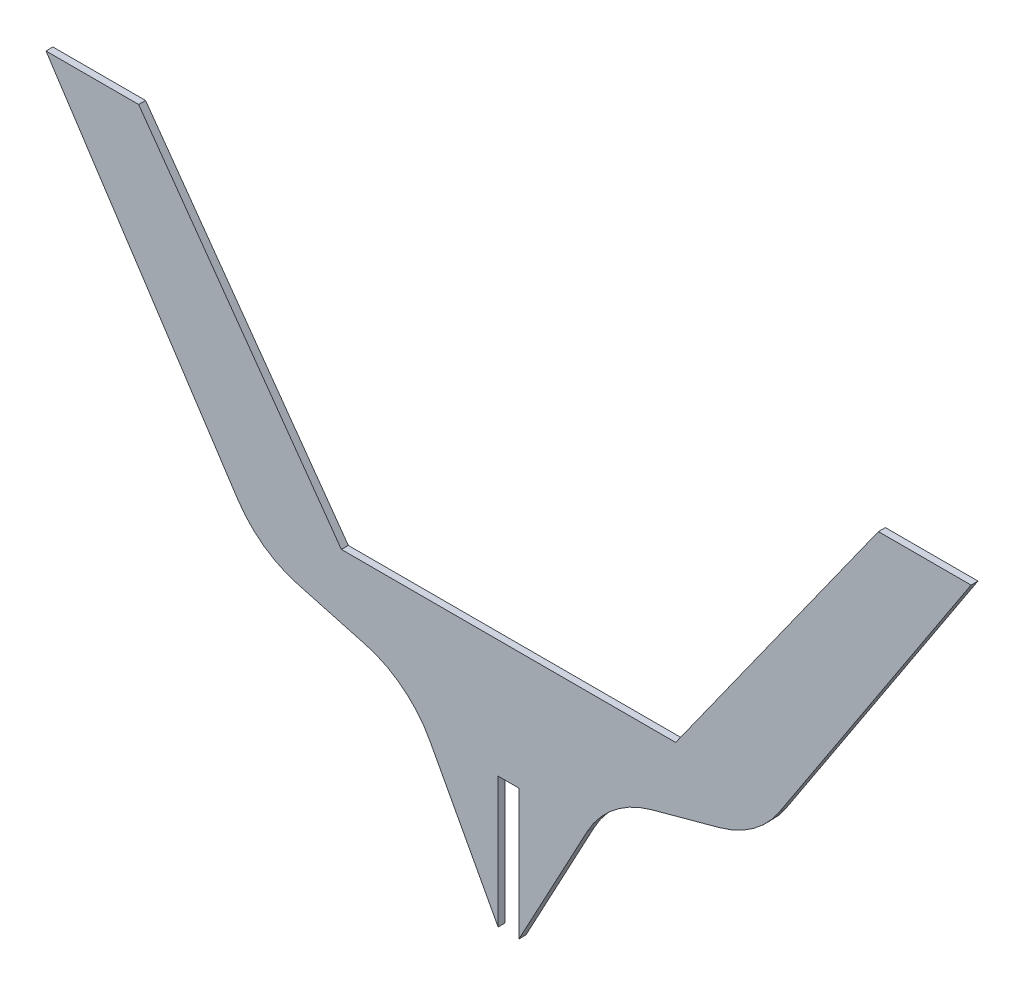
SolidWorks part; units mm, degrees
ref_plane "Plan de face" through (0, 0, 0) normal (0, 0, 1) x (1, 0, 0)
ref_plane "Plan de dessus" through (0, 0, 0) normal (0, 1, 0) x (1, 0, 0)
ref_plane "Plan de droite" through (0, 0, 0) normal (1, 0, 0) x (0, 0, -1)
sketch "Esquisse3" plane through (0, 0, 0) normal (0, 0, 1) x (1, 0, 0)
  line L46 (45.5101, -47.7781) -> (133.182, -170.5717)
  line L48 (5.4584, -47.7781) -> (97.7493, -188.5196)
  line L49 (97.7493, -188.5196) -> (162.3121, -206.0781)
  line L50 (162.3121, -206.0781) -> (200.9584, -278.0781)
  line L51 (200.9584, -278.0781) -> (200.9584, -221.5781)
  line L54 (205.4584, -221.5781) -> (205.4584, 18.2487) construction
  line L67 (5.4584, -47.7781) -> (45.5101, -47.7781)
  line L68 (133.182, -170.5717) -> (277.7348, -170.5717)
  line L69 (200.9584, -221.5781) -> (209.9584, -221.5781)
  line L70 (405.4584, -47.7781) -> (365.4068, -47.7781)
  line L71 (209.9584, -278.0781) -> (209.9584, -221.5781)
  line L72 (248.6048, -206.0781) -> (209.9584, -278.0781)
  line L73 (313.1676, -188.5196) -> (248.6048, -206.0781)
  line L74 (405.4584, -47.7781) -> (313.1676, -188.5196)
  line L75 (365.4068, -47.7781) -> (277.7348, -170.5717)
  point P6 (205.4584, -170.5717)
  point P16 (55.0051, -108.12)
  point P17 (153.6603, -162.8768)
  point P18 (77.7707, -130.3527)
  point P19 (0, 0)
  point P20 (107.4419, -120.2022)
  point P21 (57.3184, -48.3686)
  point P23 (0, 0)
  point P24 (67.9459, -131.0269)
  point P25 (113.408, -119.8089)
  point P26 (45.5101, -47.7781)
  point P27 (108.0942, -124.5323)
  point P28 (162.3121, -221.5781)
  point P29 (97.7493, -188.5196)
  point P30 (123.3054, -172.3789)
  point P31 (138.7637, -169.7743)
  point P32 (133.182, -170.5717)
  dimension "D1" = 400
  dimension "D2" = 9
  dimension "D3" = 173.8
  dimension "D4" = 56.5
extrude "Boss.-Extru.3" add sketch "Esquisse3" along normal blind 3
fillet "Congé1" radius 45 4 edges at (313.1676, -188.5196, 1.5) (248.6048, -206.0781, 1.5) (162.3121, -206.0781, 1.5) (97.7493, -188.5196, 1.5)
